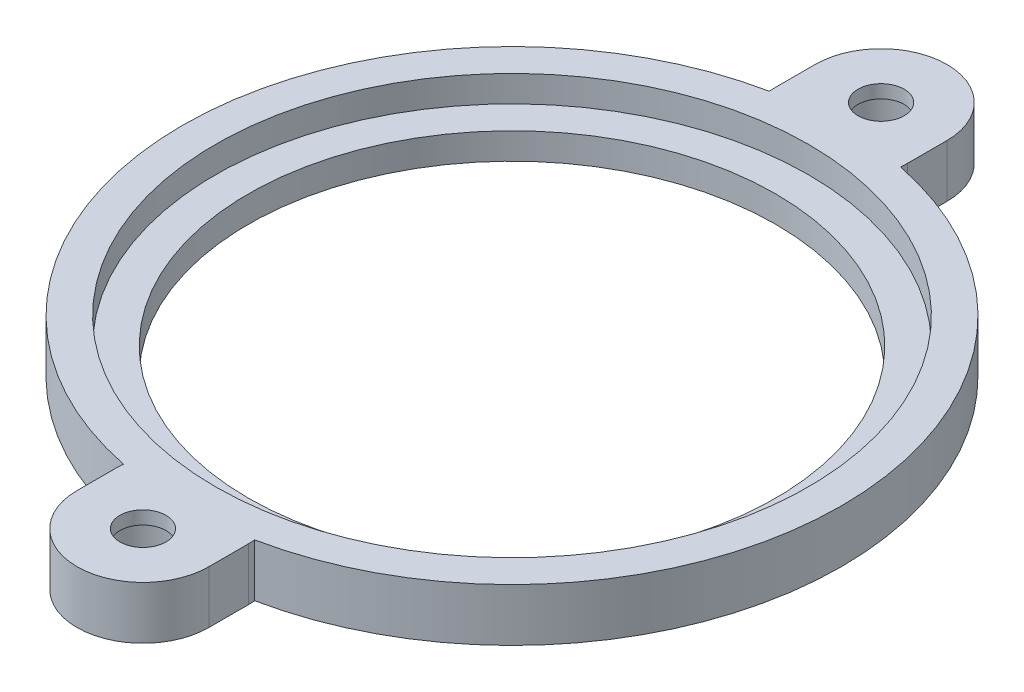
SolidWorks part; units mm, degrees
ref_plane "Front Plane" through (0, 0, 0) normal (0, 0, 1) x (1, 0, 0)
ref_plane "Top Plane" through (0, 0, 0) normal (0, 1, 0) x (1, 0, 0)
ref_plane "Right Plane" through (0, 0, 0) normal (1, 0, 0) x (0, 0, -1)
sketch "Sketch1" plane through (0, 0, 0) normal (0, 1, 0) x (1, 0, 0)
  line L0 (0, 25) -> (0, 28) construction
  line L1 (-5, 25) -> (-5, 28)
  line L2 (5, 25) -> (5, 28)
  line L3 (0, 0) -> (30.6188, 0) construction
  line L4 (0, -25) -> (0, -28) construction
  line L5 (5, -25) -> (5, -28)
  line L6 (-5, -25) -> (-5, -28)
  arc A0 (-4.9749, 24.5) -> (-4.9749, -24.5) centre (0, 0) ccw
  arc A1 (-5, 25) -> (-4.9749, 24.5) centre (0, 25) ccw
  arc A2 (5, 28) -> (-5, 28) centre (0, 28) ccw
  arc A3 (4.9749, 24.5) -> (5, 25) centre (0, 25) ccw
  arc A4 (4.9749, -24.5) -> (5, -25) centre (0, -25) cw
  arc A5 (5, -28) -> (-5, -28) centre (0, -28) cw
  arc A6 (-5, -25) -> (-4.9749, -24.5) centre (0, -25) cw
  arc A7 (4.9749, -24.5) -> (4.9749, 24.5) centre (0, 0) ccw
  point P5 (0, 26.5)
  point P20 (0, -26.5)
  dimension "D1" = 50
  dimension "D3" = 5
  dimension "D2" = 3
extrude "Boss-Extrude1" add sketch "Sketch1" along normal blind 4
sketch "Sketch2" plane through (0, 4, 0) normal (0, 1, 0) x (1, 0, 0)
  circle A0 centre (0, 0) radius 20
  dimension "D1" = 40
extrude "Cut-Extrude1" cut sketch "Sketch2" against normal through all
sketch "Sketch3" plane through (0, 4, 0) normal (0, 1, 0) x (1, 0, 0)
  circle A0 centre (0, 0) radius 22.5
  dimension "D1" = 45
extrude "Cut-Extrude2" cut sketch "Sketch3" against normal blind 2
sketch "Sketch4" plane through (0, 4, 0) normal (0, 1, 0) x (1, 0, 0)
  line L0 (0, 0) -> (-33.6332, 0) construction
  circle A0 centre (0, -28) radius 1.75
  circle A1 centre (0, 28) radius 1.75
  dimension "D1" = 3.5
extrude "Cut-Extrude3" cut sketch "Sketch4" against normal through all
sketch "Sketch5" plane through (0, 0, 0) normal (0, -1, 0) x (1, 0, 0)
  line L0 (0, 0) -> (0, 45.1467) construction
  line L1 (0, 0) -> (29.4053, 0) construction
  circle A0 centre (0, 28) radius 3.25
  circle A1 centre (0, -28) radius 3.25
  dimension "D1" = 6.5
extrude "Cut-Extrude4" cut sketch "Sketch5" against normal blind 3
